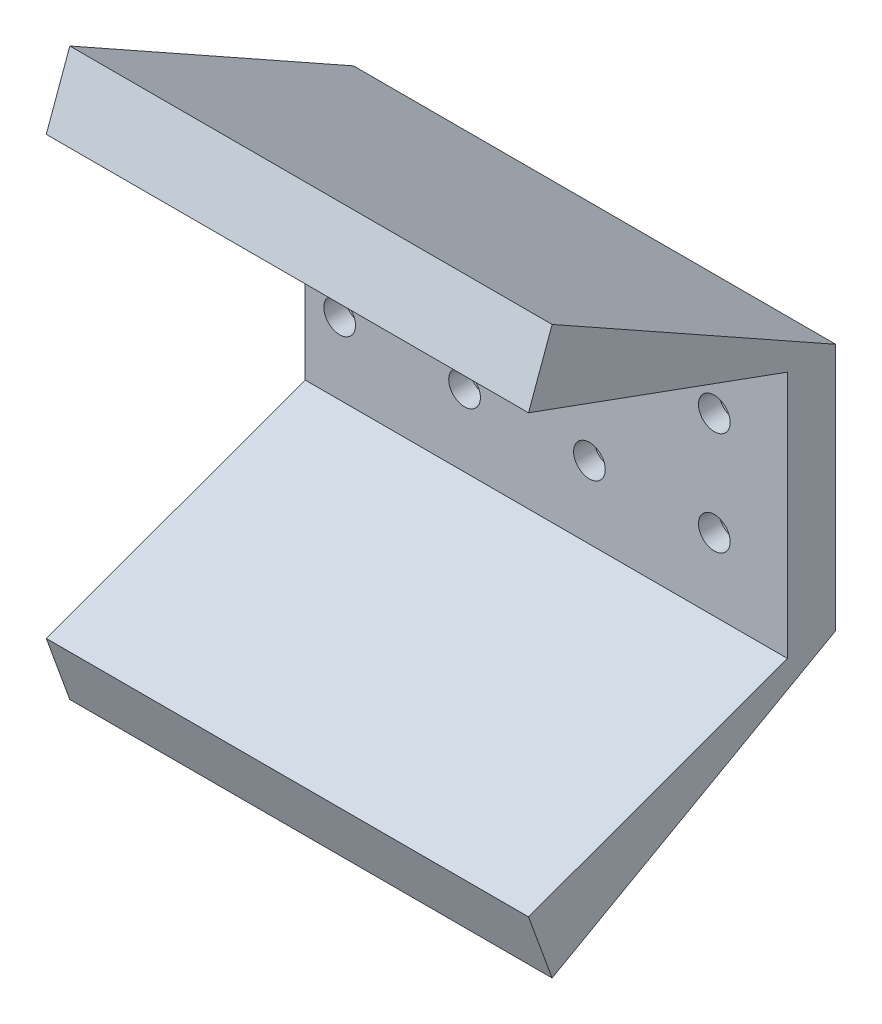
SolidWorks part; units mm, degrees
ref_plane "Plan de face" through (0, 0, 0) normal (0, 0, 1) x (1, 0, 0)
ref_plane "Plan de dessus" through (0, 0, 0) normal (0, 1, 0) x (1, 0, 0)
ref_plane "Plan de droite" through (0, 0, 0) normal (1, 0, 0) x (0, 0, -1)
sketch "Esquisse1" plane through (0, 0, 0) normal (0, 0, 1) x (1, 0, 0)
  line L0 (0, 0) -> (70, 0)
  line L1 (0, 0) -> (0, 36)
  line L2 (70, 0) -> (70, 36)
  line L3 (0, 36) -> (70, 36)
  line L4 (0, 25.5) -> (70, 25.5) construction
  line L5 (0, 10.5) -> (70, 10.5) construction
  line L6 (5, 25.5) -> (5, 10.5) construction
  line L8 (23.125, 25.5) -> (23.125, 10.5) construction
  line L10 (41.25, 25.5) -> (41.25, 10.5) construction
  line L12 (59.375, 25.5) -> (59.375, 10.5) construction
  circle A0 centre (5, 25.5) radius 2.3
  circle A1 centre (5, 10.5) radius 2.3
  circle A2 centre (23.125, 25.5) radius 2.3
  circle A3 centre (23.125, 10.5) radius 2.3
  circle A4 centre (41.25, 25.5) radius 2.3
  circle A5 centre (41.25, 10.5) radius 2.3
  circle A6 centre (59.375, 25.5) radius 2.3
  circle A7 centre (59.375, 10.5) radius 2.3
  point P27 (88.4633, 37.9035)
  dimension "D9" = 4.6
  dimension "D1" = 10.5
  dimension "D2" = 15
  dimension "D3" = 36
  dimension "D4" = 70
  dimension "D5" = 5
  dimension "D6" = 18.125
  dimension "D7" = 18.125
  dimension "D8" = 18.125
extrude "Boss.-Extru.1" add sketch "Esquisse1" along normal blind 7
sketch "Esquisse2" plane through (0, 0, 0) normal (0, 0, -1) x (-1, 0, 0)
  circle A0 centre (-59.375, 25.5) radius 4
  circle A1 centre (-41.25, 25.5) radius 4
  circle A2 centre (-23.125, 25.5) radius 4
  circle A3 centre (-5, 25.5) radius 4
  circle A4 centre (-5, 10.5) radius 4
  circle A5 centre (-23.125, 10.5) radius 4
  circle A6 centre (-41.25, 10.5) radius 4
  circle A7 centre (-59.375, 10.5) radius 4
  dimension "D1" = 8
extrude "Enlèv. mat.-Extru.1" cut sketch "Esquisse2" against normal blind 4
sketch "Esquisse3" plane through (70, 0, 0) normal (1, 0, 0) x (0, 0, -1)
  line L0 (-7, 36) -> (-44.5877, 49.6808)
  line L1 (-44.5877, 49.6808) -> (-41.1675, 59.0777)
  line L2 (-41.1675, 59.0777) -> (0, 36)
  line L3 (-7, 0) -> (-44.5877, -13.6808)
  line L4 (-44.5877, -13.6808) -> (-41.1675, -23.0777)
  line L5 (-41.1675, -23.0777) -> (0, 0)
  line L6 (-7, 0) -> (-7, 36) construction
  line L7 (-6.5294, 0) -> (0, 0)
  line L8 (-7, 0) -> (0, 0) construction
  line L9 (0, 36) -> (-7, 36)
  line L10 (-34.0471, 18) -> (-7, 18) construction
  circle A0 centre (-34.0471, 18) radius 21
  point P19 (-28.9146, 18)
  point P21 (-34.1519, 18)
  line M8 (0, 36) -> (-7, 36)
  line M10 (-7, 0) -> (0, 0)
  dimension "D7" = 42
  dimension "D1" = 10
  dimension "D2" = 10
  dimension "D3" = 110
  dimension "D4" = 110
  dimension "D5" = 40
  dimension "D6" = 40
extrude "Boss.-Extru.2" add sketch "Esquisse3" against normal blind 70 contours L2 L1 L0 M8 | L4 L5 L3 M10
